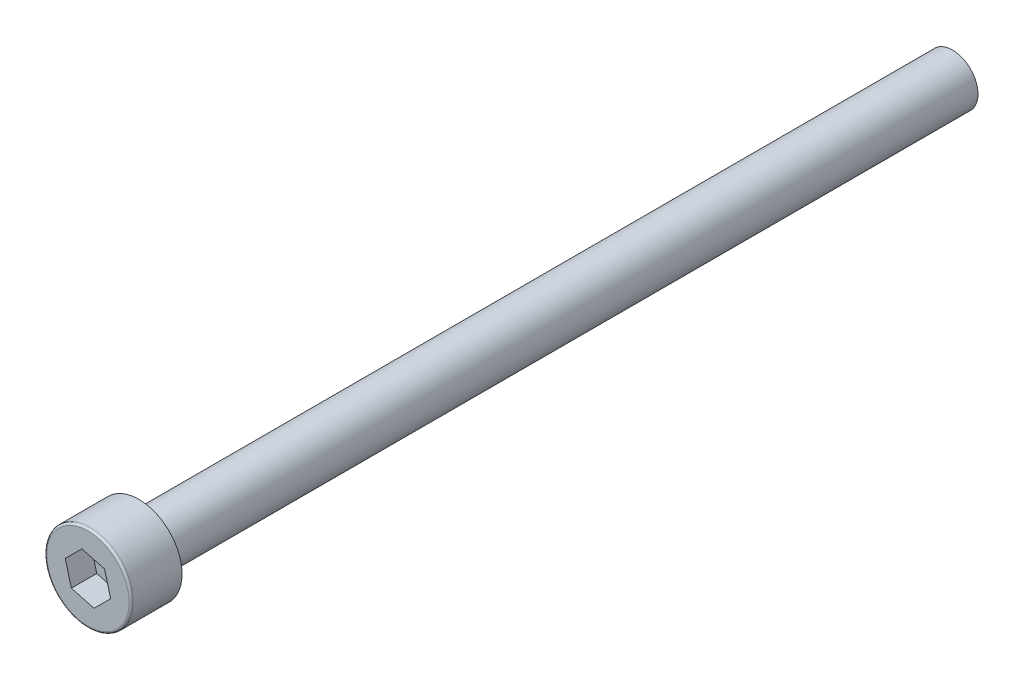
SolidWorks part; units mm, degrees
ref_plane "前视基准面" through (0, 0, 0) normal (0, 0, 1) x (1, 0, 0)
ref_plane "上视基准面" through (0, 0, 0) normal (0, 1, 0) x (1, 0, 0)
ref_plane "右视基准面" through (0, 0, 0) normal (1, 0, 0) x (0, 0, -1)
sketch "草图1" plane through (0, 0, 0) normal (0, 0, 1) x (1, 0, 0)
  circle A0 centre (0, 0) radius 4.25
  dimension "D1" = 8.5
extrude "凸台-拉伸1" add sketch "草图1" along normal blind 5
sketch "草图2" plane through (0, 0, 5) normal (0, 0, 1) x (1, 0, 0)
  line L1 (-1.633, -1.633) -> (0.5977, -2.2307)
  line L2 (0.5977, -2.2307) -> (2.2307, -0.5977)
  line L3 (2.2307, -0.5977) -> (1.633, 1.633)
  line L4 (1.633, 1.633) -> (-0.5977, 2.2307)
  line L5 (-0.5977, 2.2307) -> (-2.2307, 0.5977)
  line L6 (-2.2307, 0.5977) -> (-1.633, -1.633)
  circle A0 centre (0, 0) radius 2 construction
  dimension "D1" = 4
extrude "切除-拉伸1" cut sketch "草图2" against normal blind 2.5
sketch "草图3" plane through (0, 0, 0) normal (0, 0, -1) x (-1, 0, 0)
  circle A0 centre (0, 0) radius 2.5
  dimension "D1" = 5
extrude "凸台-拉伸2" add sketch "草图3" along normal blind 80
fillet "圆角1" radius 0.2 1 edges at (4.25, 0, 5)
